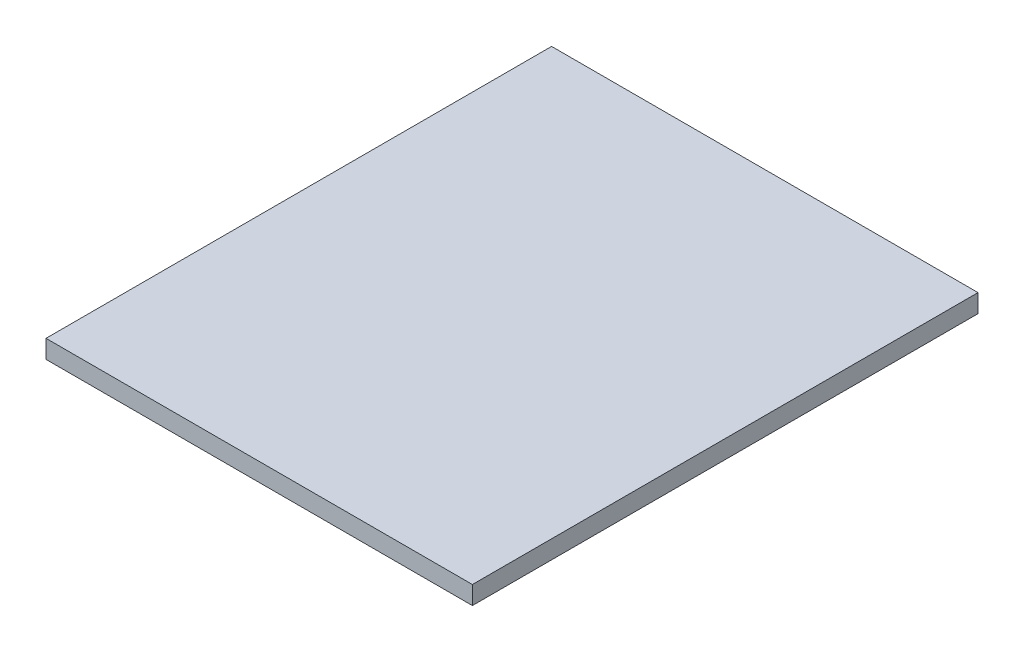
SolidWorks part; units mm, degrees
ref_plane "Front Plane" through (0, 0, 0) normal (0, 0, 1) x (1, 0, 0)
ref_plane "Top Plane" through (0, 0, 0) normal (0, 1, 0) x (1, 0, 0)
ref_plane "Right Plane" through (0, 0, 0) normal (1, 0, 0) x (0, 0, -1)
sketch "Sketch1" plane through (0, 0, 0) normal (0, 1, 0) x (1, 0, 0)
  line L1 (35, 41.5) -> (-35, 41.5)
  line L2 (35, 41.5) -> (35, -41.5)
  line L3 (35, -41.5) -> (-35, -41.5)
  line L4 (-35, 41.5) -> (-35, -41.5)
  line L5 (35, 41.5) -> (-35, -41.5) construction
  line L6 (35, -41.5) -> (-35, 41.5) construction
  point P0 (0, 0)
  dimension "D1" = 70
  dimension "D2" = 83
extrude "Boss-Extrude1" add sketch "Sketch1" along normal blind 3
